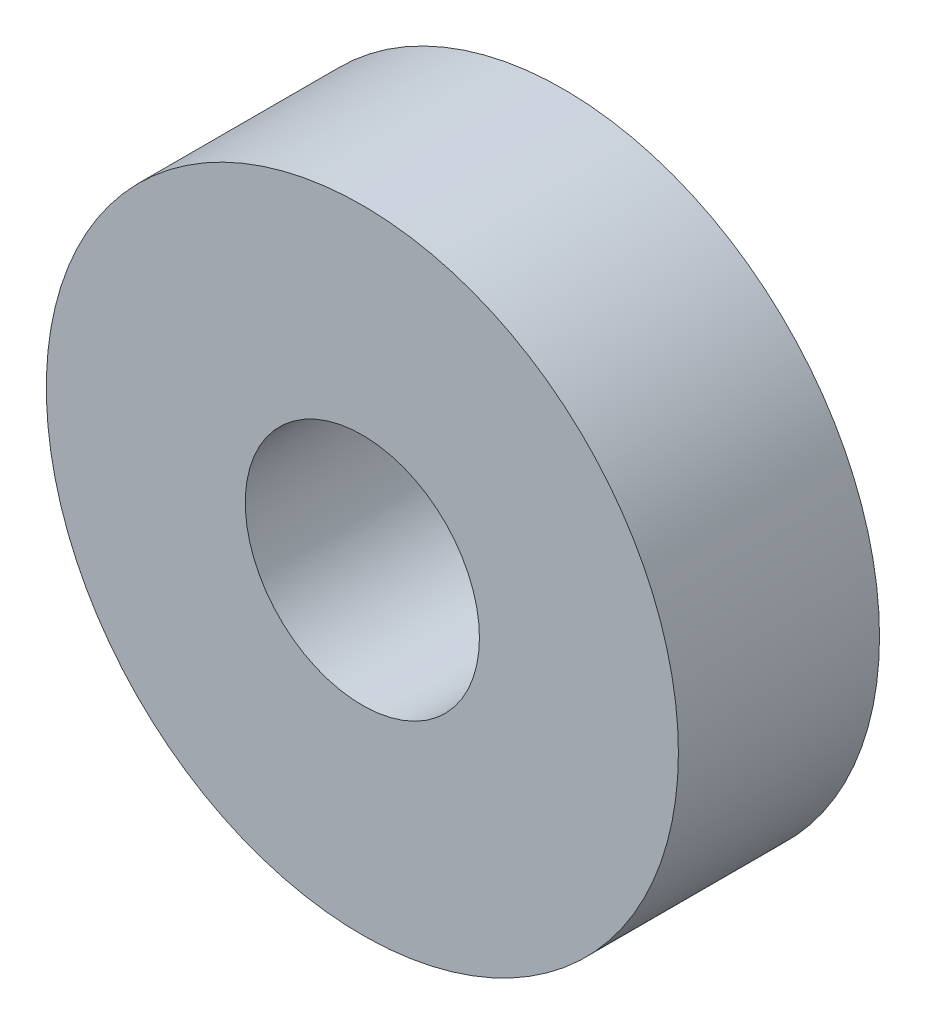
SolidWorks part; units mm, degrees
ref_plane "Plan de face" through (0, 0, 0) normal (0, 0, 1) x (1, 0, 0)
ref_plane "Plan de dessus" through (0, 0, 0) normal (0, 1, 0) x (1, 0, 0)
ref_plane "Plan de droite" through (0, 0, 0) normal (1, 0, 0) x (0, 0, -1)
sketch "Esquisse1" plane through (0, 0, 0) normal (0, 0, 1) x (1, 0, 0)
  circle A0 centre (0, 0) radius 11
  circle A1 centre (0, 0) radius 4.075
  dimension "D1" = 8.15
  dimension "D2" = 22
extrude "Boss.-Extru.1" add sketch "Esquisse1" along normal blind 7
